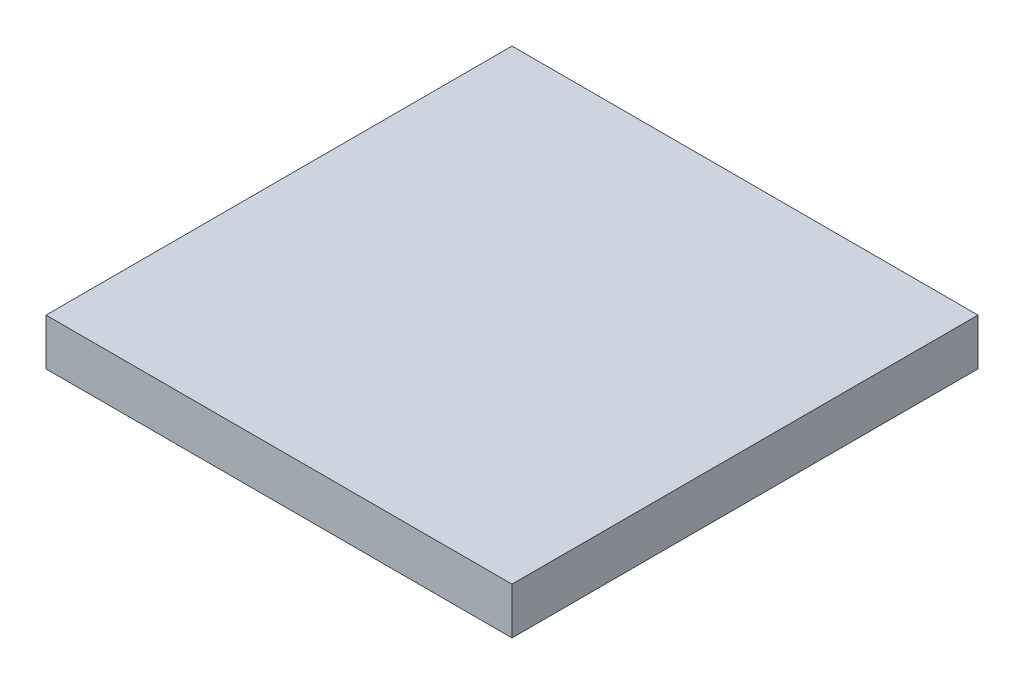
SolidWorks part; units mm, degrees
ref_plane "Front Plane" through (0, 0, 0) normal (0, 0, 1) x (1, 0, 0)
ref_plane "Top Plane" through (0, 0, 0) normal (0, 1, 0) x (1, 0, 0)
ref_plane "Right Plane" through (0, 0, 0) normal (1, 0, 0) x (0, 0, -1)
sketch "Sketch1" plane through (0, 0, 0) normal (0, 1, 0) x (1, 0, 0)
  line L1 (0, 0) -> (25.4, 0)
  line L2 (0, 0) -> (0, 25.4)
  line L3 (0, 25.4) -> (25.4, 25.4)
  line L4 (25.4, 0) -> (25.4, 25.4)
  dimension "D1" = 25.4
  dimension "D2" = 25.4
extrude "Boss-Extrude1" add sketch "Sketch1" along normal blind 2.54
